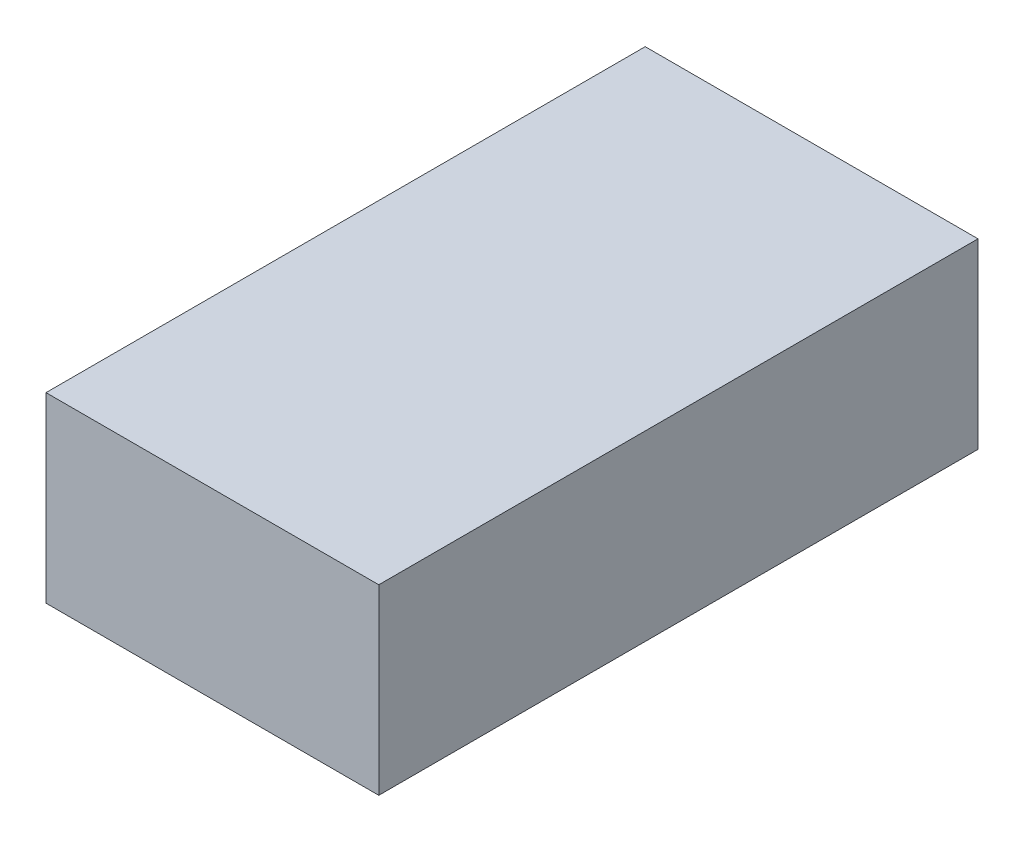
SolidWorks part; units mm, degrees
ref_plane "Front Plane" through (0, 0, 0) normal (0, 0, 1) x (1, 0, 0)
ref_plane "Top Plane" through (0, 0, 0) normal (0, 1, 0) x (1, 0, 0)
ref_plane "Right Plane" through (0, 0, 0) normal (1, 0, 0) x (0, 0, -1)
sketch "CurveSketch" plane through (0, 0, 0) normal (0, 0, 1) x (1, 0, 0)
  line L0 (-20.0525, -1.8635) -> (11.6665, -1.8635)
  line L1 (11.6665, -1.8635) -> (11.6665, 15.5175)
  line L2 (11.6665, 15.5175) -> (-20.0525, 15.5175)
  line L3 (-20.0525, 15.5175) -> (-20.0525, -1.8635)
extrude "CurveBoss" add sketch "CurveSketch" against normal blind 57.113
